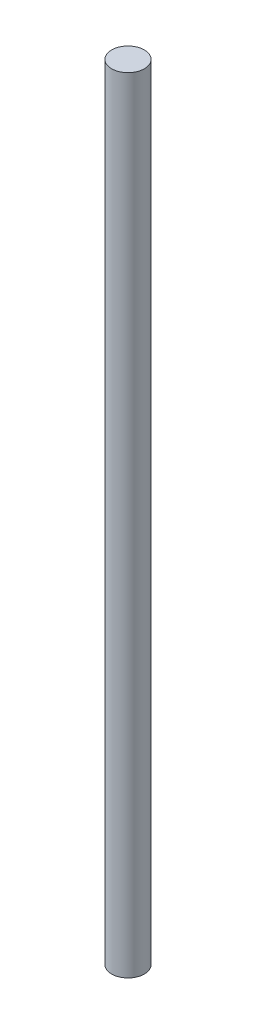
SolidWorks part; units mm, degrees
ref_plane "Front Plane" through (0, 0, 0) normal (0, 0, 1) x (1, 0, 0)
ref_plane "Top Plane" through (0, 0, 0) normal (0, 1, 0) x (1, 0, 0)
ref_plane "Right Plane" through (0, 0, 0) normal (1, 0, 0) x (0, 0, -1)
sketch "Sketch1" plane through (0, 0, 0) normal (0, 1, 0) x (1, 0, 0)
  circle A0 centre (0, 0) radius 6.35
extrude "Boss-Extrude1" add sketch "Sketch1" along normal blind 304.8
